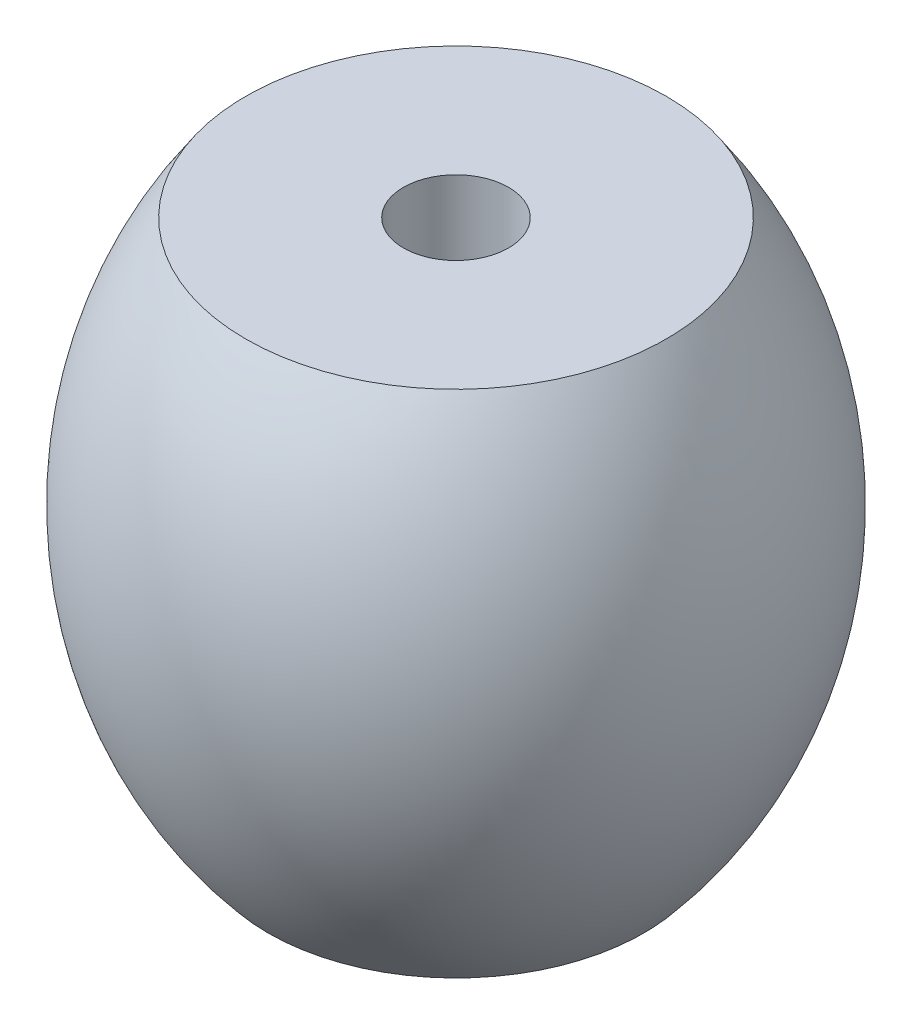
SolidWorks part; units mm, degrees
ref_plane "Front Plane" through (0, 0, 0) normal (0, 0, 1) x (1, 0, 0)
ref_plane "Top Plane" through (0, 0, 0) normal (0, 1, 0) x (1, 0, 0)
ref_plane "Right Plane" through (0, 0, 0) normal (1, 0, 0) x (0, 0, -1)
sketch "Sketch1" plane through (0, 0, 0) normal (0, 0, 1) x (1, 0, 0)
  line L0 (0, 0) -> (0, 10) construction
  line L1 (-1, 10) -> (-4, 10)
  line L2 (-3.5746, 0) -> (-2, 0)
  line L3 (-2, 0) -> (-2, 2)
  line L4 (-2, 2) -> (-3.7152, 2)
  line L5 (-1, 10) -> (-1, 7)
  line L6 (-1, 7) -> (-4.2963, 7)
  arc A0 (-4, 10) -> (-3.5746, 0) centre (2.6547, 5.2741) ccw
  arc A1 (-4.2963, 7) -> (-3.7152, 2) centre (2.6547, 5.2741) ccw
  point P6 (0, 0)
  point P14 (-5.5, 4.9271)
  point P15 (-2, -0.623)
  dimension "D1" = 1
  dimension "D4" = 5.5
  dimension "D2" = 3
  dimension "D3" = 2
  dimension "D5" = 1
  dimension "D6" = 2
  dimension "D7" = 10
  dimension "D8" = 3
  dimension "D9" = 3.2963
revolve "Revolve1" add sketch "Sketch1" angle 360 about L0
